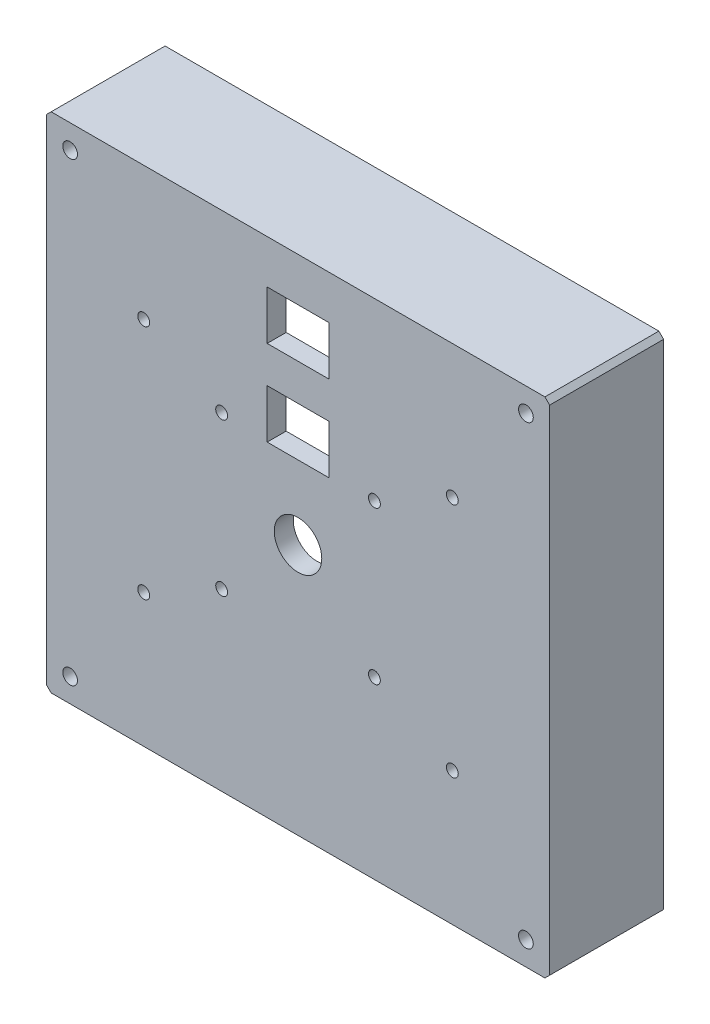
SolidWorks part; units mm, degrees
ref_plane "Front Plane" through (0, 0, 0) normal (0, 0, 1) x (1, 0, 0)
ref_plane "Top Plane" through (0, 0, 0) normal (0, 1, 0) x (1, 0, 0)
ref_plane "Right Plane" through (0, 0, 0) normal (1, 0, 0) x (0, 0, -1)
sketch "Sketch1" plane through (0, 0, 0) normal (0, 0, 1) x (1, 0, 0)
  line L0 (0, 43) -> (0, -43) construction
  line L1 (-53, 53) -> (53, 53)
  line L2 (-53, 53) -> (-53, -53)
  line L3 (-53, -53) -> (53, -53)
  line L4 (53, 53) -> (53, -53)
  line L5 (-43, 0) -> (43, 0) construction
  point P5 (-53, 0)
  point P7 (0, 53)
  dimension "D1" = 106
  dimension "D2" = 106
extrude "Boss-Extrude1" add sketch "Sketch1" against normal blind 4
sketch "Sketch2" plane through (0, 0, -4) normal (0, 0, -1) x (-1, 0, 0)
  line L0 (53, 53) -> (53, -53) construction
  line L1 (-53, 53) -> (53, 53)
  line L2 (-53, 53) -> (-53, -53)
  line L3 (-53, -53) -> (53, -53)
  line L4 (53, 53) -> (53, -53)
  line L5 (-48, 41) -> (-48, -41)
  line L10 (-48, -41) -> (-41, -48)
  line L11 (-41, -48) -> (41, -48)
  line L12 (41, -48) -> (48, -41)
  line L13 (48, -41) -> (48, 41)
  line L14 (48, 41) -> (41, 48)
  line L15 (41, 48) -> (-41, 48)
  line L16 (-41, 48) -> (-48, 41)
  dimension "D1" = 5
  dimension "D2" = 5
  dimension "D3" = 5
  dimension "D4" = 5
  dimension "D5" = 12
  dimension "D6" = 12
  dimension "D7" = 12
  dimension "D8" = 12
  dimension "D9" = 12
extrude "Boss-Extrude2" add sketch "Sketch2" along normal blind 20
sketch "Sketch6" plane through (0, 0, 0) normal (0, 0, 1) x (1, 0, 0)
  line L1 (-53, 53) -> (53, 53)
  line L2 (-53, 53) -> (-53, -53)
  line L3 (-53, -53) -> (53, -53)
  line L4 (53, 53) -> (53, -53)
  circle A0 centre (0, 0) radius 48
  dimension "D1" = 96
sketch "Sketch7" plane through (0, 0, 0) normal (0, 0, 1) x (1, 0, 0)
  line L1 (-53, 53) -> (53, 53) construction
  line L2 (-53, 53) -> (-53, -53) construction
  line L3 (-53, -53) -> (53, -53) construction
  line L4 (53, 53) -> (53, -53) construction
  circle A0 centre (-48, 48) radius 1.55
  circle A1 centre (48, 48) radius 1.55
  circle A2 centre (-48, -48) radius 1.55
  circle A3 centre (48, -48) radius 1.55
  dimension "D1" = 5
  dimension "D3" = 3.1
  dimension "D6" = 3.1
  dimension "D9" = 3.1
  dimension "D12" = 3.1
  dimension "D2" = 5
  dimension "D4" = 5
  dimension "D5" = 5
  dimension "D7" = 5
  dimension "D8" = 5
  dimension "D10" = 5
  dimension "D11" = 5
extrude "Cut-Extrude2" cut sketch "Sketch7" against normal blind 50
sketch "Sketch8" plane through (0, 0, 0) normal (0, 0, 1) x (1, 0, 0)
  line L0 (-16.0867, -16.0867) -> (16.0867, 16.0867) construction
  line L1 (-6.5, 43.8) -> (6.5, 43.8)
  line L2 (-6.5, 43.8) -> (-6.5, 33.5)
  line L3 (-6.5, 33.5) -> (6.5, 33.5)
  line L4 (6.5, 43.8) -> (6.5, 33.5)
  line L5 (-6.5, 25.8) -> (6.5, 25.8)
  line L6 (-6.5, 25.8) -> (-6.5, 15.5)
  line L7 (-6.5, 15.5) -> (6.5, 15.5)
  line L8 (6.5, 25.8) -> (6.5, 15.5)
  line L9 (-16.0867, 16.0867) -> (16.0867, -16.0867) construction
  line L10 (0, 53) -> (0, -53) construction
  line L11 (-53, 53) -> (53, 53) construction
  line L12 (-53, 53) -> (-53, -53) construction
  line L13 (-53, -53) -> (53, -53) construction
  line L14 (53, 53) -> (53, -53) construction
  line L15 (13.2, 0) -> (-13.2, 0) construction
  line L16 (-4.5, 23.8) -> (4.5, 23.8) construction
  line L17 (-4.5, 23.8) -> (-4.5, 21.5) construction
  line L18 (-4.5, 21.5) -> (4.5, 21.5) construction
  line L19 (4.5, 23.8) -> (4.5, 21.5) construction
  line L20 (-4.5, 41.8) -> (4.5, 41.8) construction
  line L21 (-4.5, 41.8) -> (-4.5, 39.5) construction
  line L22 (-4.5, 39.5) -> (4.5, 39.5) construction
  line L23 (4.5, 41.8) -> (4.5, 39.5) construction
  line L24 (-32.5, 24.9) -> (32.5, 24.9) construction
  line L25 (-32.5, 24.9) -> (-32.5, -24.9) construction
  line L26 (-32.5, -24.9) -> (32.5, -24.9) construction
  line L27 (32.5, 24.9) -> (32.5, -24.9) construction
  line L28 (-53, 0) -> (53, 0) construction
  circle A0 centre (32.5, 24.9) radius 1.25
  circle A1 centre (-32.5, 24.9) radius 1.25
  circle A2 centre (-32.5, -24.9) radius 1.25
  circle A3 centre (32.5, -24.9) radius 1.25
  circle A4 centre (16.0867, -16.0867) radius 1.25
  circle A5 centre (-16.0867, -16.0867) radius 1.25
  circle A6 centre (16.0867, 16.0867) radius 1.25
  circle A7 centre (-16.0867, 16.0867) radius 1.25
  circle A8 centre (0, 0) radius 5
  point P22 (32.5, 0)
  point P25 (-32.5, 0)
  dimension "D6" = 2.5
  dimension "D7" = 2.5
  dimension "D8" = 2.5
  dimension "D9" = 2.5
  dimension "D10" = 2.5
  dimension "D11" = 2.5
  dimension "D12" = 2.5
  dimension "D13" = 2.5
  dimension "D22" = 10
  dimension "D1" = 65
  dimension "D2" = 49.8
  dimension "D3" = 45.5
  dimension "D4" = 45.5
  dimension "D5" = 45
  dimension "D14" = 2
  dimension "D15" = 6
  dimension "D16" = 2
  dimension "D17" = 2
  dimension "D18" = 2
  dimension "D19" = 6
  dimension "D20" = 2
  dimension "D21" = 2
extrude "Cut-Extrude3" cut sketch "Sketch8" against normal blind 10
sketch "Sketch9" plane through (0, 0, -4) normal (0, 0, 1) x (1, 0, 0)
  line L0 (0, 46) -> (0, -46) construction
  line L1 (-53, 53) -> (53, 53) construction
  line L2 (-53, 53) -> (-53, -53) construction
  line L3 (-53, -53) -> (53, -53) construction
  line L4 (53, 53) -> (53, -53) construction
  line L5 (-39.5, 46) -> (39.5, 46) construction
  line L6 (-39.5, 46) -> (-39.5, -46) construction
  line L7 (-39.5, -46) -> (39.5, -46) construction
  line L8 (39.5, 46) -> (39.5, -46) construction
  line L9 (-39.5, 0) -> (39.5, 0) construction
  line L18 (37.4, 39.7988) -> (35.7012, 38.1)
  line L19 (-35.7012, 38.1) -> (-33.2988, 38.1)
  line L20 (-33.2988, 38.1) -> (-31.6, 39.7988)
  line L21 (-31.6, 39.7988) -> (-31.6, 42.2012)
  line L22 (-31.6, 42.2012) -> (-33.2988, 43.9)
  line L23 (-33.2988, 43.9) -> (-35.7012, 43.9)
  line L24 (-35.7012, 43.9) -> (-37.4, 42.2012)
  line L25 (-37.4, 42.2012) -> (-37.4, 39.7988)
  line L26 (-37.4, 39.7988) -> (-35.7012, 38.1)
  line L27 (37.4, 42.2012) -> (37.4, 39.7988)
  line L28 (35.7012, 43.9) -> (37.4, 42.2012)
  line L29 (33.2988, 43.9) -> (35.7012, 43.9)
  line L30 (31.6, 42.2012) -> (33.2988, 43.9)
  line L31 (31.6, 39.7988) -> (31.6, 42.2012)
  line L32 (33.2988, 38.1) -> (31.6, 39.7988)
  line L33 (35.7012, 38.1) -> (33.2988, 38.1)
  line L34 (35.7012, -38.1) -> (33.2988, -38.1)
  line L35 (33.2988, -38.1) -> (31.6, -39.7988)
  line L36 (31.6, -39.7988) -> (31.6, -42.2012)
  line L37 (31.6, -42.2012) -> (33.2988, -43.9)
  line L38 (33.2988, -43.9) -> (35.7012, -43.9)
  line L39 (35.7012, -43.9) -> (37.4, -42.2012)
  line L40 (37.4, -42.2012) -> (37.4, -39.7988)
  line L41 (37.4, -39.7988) -> (35.7012, -38.1)
  line L42 (-37.4, -39.7988) -> (-35.7012, -38.1)
  line L43 (-37.4, -42.2012) -> (-37.4, -39.7988)
  line L44 (-35.7012, -43.9) -> (-37.4, -42.2012)
  line L45 (-33.2988, -43.9) -> (-35.7012, -43.9)
  line L46 (-31.6, -42.2012) -> (-33.2988, -43.9)
  line L47 (-31.6, -39.7988) -> (-31.6, -42.2012)
  line L48 (-33.2988, -38.1) -> (-31.6, -39.7988)
  line L49 (-35.7012, -38.1) -> (-33.2988, -38.1)
  circle A0 centre (-34.5, 41) radius 4.5
  circle A4 centre (-34.5, 41) radius 2.9 construction
  circle A5 centre (34.5, 41) radius 4.5
  circle A6 centre (34.5, -41) radius 4.5
  circle A7 centre (-34.5, -41) radius 2.9 construction
  circle A8 centre (-34.5, -41) radius 4.5
  dimension "D1" = 9
  dimension "D2" = 13.5
  dimension "D3" = 13.5
  dimension "D4" = 7
  dimension "D5" = 7
  dimension "D6" = 5
  dimension "D7" = 5
  dimension "D8" = 5.8
extrude "Boss-Extrude3" add sketch "Sketch9" against normal blind 4
sketch "Sketch14" plane through (0, -53, 0) normal (0, -1, 0) x (1, 0, 0)
  line L0 (0, 0) -> (0, -24) construction
  line L5 (-53, 0) -> (53, 0) construction
  line L6 (-53, 0) -> (-53, -24) construction
  line L7 (-53, -24) -> (53, -24) construction
  line L8 (53, 0) -> (53, -24) construction
  line L10 (-6.5, -10.83) -> (6.5, -10.83) construction
  line L13 (-6.5, -6.83) -> (6.5, -6.83)
  line L14 (-6.5, -6.83) -> (-6.5, -14.83)
  line L15 (-6.5, -14.83) -> (6.5, -14.83)
  line L16 (6.5, -6.83) -> (6.5, -14.83)
  circle A0 centre (20, -18) radius 2.75
  point P10 (-6.5, -10.83)
  point P13 (6.5, -10.83)
  point P14 (0, -14.83)
  point P19 (0, 0)
  dimension "D4" = 5.5
  dimension "D1" = 10.83
  dimension "D2" = 13
  dimension "D3" = 8
  dimension "D5" = 20
  dimension "D6" = 18
extrude "Cut-Extrude4" cut sketch "Sketch14" against normal blind 10
chamfer "Chamfer1" distance 1 4 edges at (53, 53, -12) (-53, 53, -12) (-53, -53, -12) (53, -53, -12)
chamfer "Chamfer2" distance 1 4 edges at (0, -53, -6.83) (6.5, -53, -10.83) (0, -53, -14.83) (-6.5, -53, -10.83)
sketch "Sketch15" plane through (48, 0, 0) normal (-1, 0, 0) x (0, 0, 1)
  line L0 (-12, -53) -> (-12, 53) construction
  line L1 (0, -53) -> (-24, -53) construction
  line L2 (0, -53) -> (0, 53) construction
  line L3 (0, 53) -> (-24, 53) construction
  line L4 (-24, -53) -> (-24, 53) construction
  circle A0 centre (-12, -23) radius 1.6
  circle A1 centre (-12, 23) radius 1.6
  dimension "D1" = 3.2
  dimension "D2" = 3.2
  dimension "D3" = 30
  dimension "D4" = 30
extrude "Cut-Extrude5" cut sketch "Sketch15" against normal blind 1 and the other way blind 97
chamfer "Chamfer3" distance 1 angle 45 2 edges at (20, -48, -15.25) (22.75, -53, -18)
